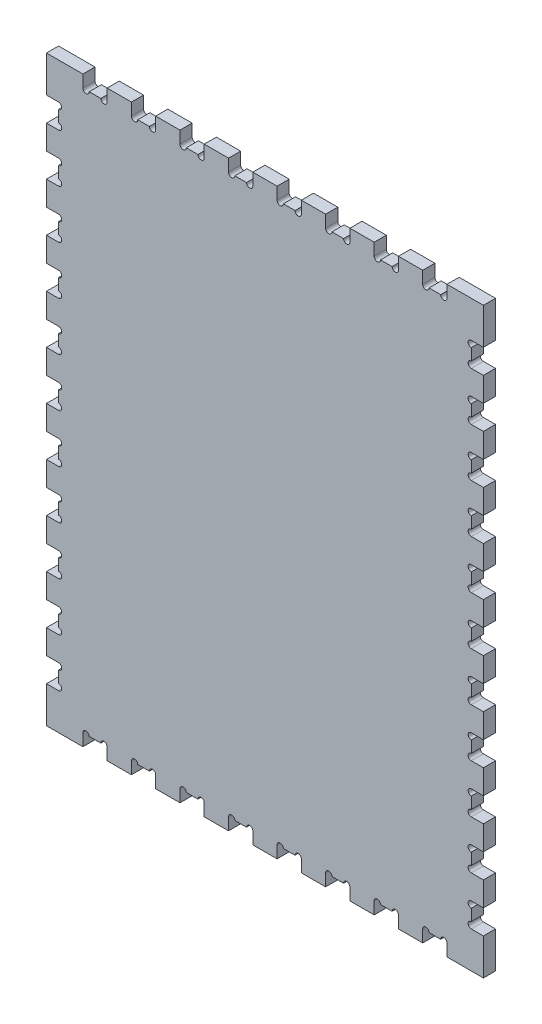
SolidWorks part; units mm, degrees
ref_plane "Front Plane" through (0, 0, 0) normal (0, 0, 1) x (1, 0, 0)
ref_plane "Top Plane" through (0, 0, 0) normal (0, 1, 0) x (1, 0, 0)
ref_plane "Right Plane" through (0, 0, 0) normal (1, 0, 0) x (0, 0, -1)
sketch "Sketch1" plane through (0, 0, 0) normal (0, 0, 1) x (1, 0, 0)
  line L1 (228.6, -304.8) -> (-228.6, -304.8)
  line L2 (228.6, -304.8) -> (228.6, 304.8)
  line L3 (228.6, 304.8) -> (-228.6, 304.8)
  line L4 (-228.6, -304.8) -> (-228.6, 304.8)
  line L5 (228.6, -304.8) -> (-228.6, 304.8) construction
  line L6 (228.6, 304.8) -> (-228.6, -304.8) construction
  line L9 (-203.2, 304.8) -> (-228.6, 304.8) construction
  point P0 (0, 0)
  point P7 (0, 0)
  dimension "D1" = 457.2
  dimension "D2" = 609.6
extrude "Boss-Extrude1" add sketch "Sketch1" along normal blind 12.7
sketch "Sketch2" plane through (0, 0, 12.7) normal (0, 0, 1) x (1, 0, 0)
  line L0 (228.6, 304.8) -> (-228.6, 304.8) construction
  line L1 (-190.5, 292.1) -> (-228.6, 292.1) construction
  line L2 (-190.5, 304.8) -> (-165.1, 304.8)
  line L3 (-190.5, 304.8) -> (-190.5, 292.1)
  line L4 (-190.5, 292.1) -> (-165.1, 292.1)
  line L5 (-165.1, 304.8) -> (-165.1, 292.1)
  line L6 (-228.6, 304.8) -> (-228.6, -304.8) construction
  circle A0 centre (-187.198, 292.1) radius 3.302
  circle A1 centre (-168.402, 292.1) radius 3.302
  point P13 (-200.025, 292.1)
  point P14 (-200.025, 292.1)
  line M10 (228.6, 304.8) -> (-228.6, 304.8)
  dimension "D4" = 6.604
  dimension "D5" = 6.604
  dimension "D1" = 25.4
  dimension "D2" = 12.7
  dimension "D3" = 38.1
extrude "Cut-Extrude1" cut sketch "Sketch2" against normal through all contours A1 L5 L3 A0 L4 M10 | L4 A0 | L4 A0 | L4 A1 | L4 A1
pattern_linear "LPattern1" count 8 spacing 50.8 along (1, 0, 0) of "Cut-Extrude1"
sketch "Sketch3" plane through (0, 0, 12.7) normal (0, 0, 1) x (1, 0, 0)
  line L0 (-228.6, 304.8) -> (-228.6, -304.8) construction
  line L1 (-228.6, 266.7) -> (-215.9, 266.7)
  line L2 (-228.6, 266.7) -> (-228.6, 241.3)
  line L3 (-228.6, 241.3) -> (-215.9, 241.3)
  line L4 (-215.9, 266.7) -> (-215.9, 241.3)
  line L5 (-215.9, 266.7) -> (-215.9, 304.8) construction
  line L7 (-190.5, 304.8) -> (-228.6, 304.8) construction
  circle A0 centre (-215.9, 263.398) radius 3.302
  circle A1 centre (-215.9, 244.602) radius 3.302
  dimension "D3" = 6.604
  dimension "D4" = 6.604
  dimension "D1" = 25.4
  dimension "D2" = 12.7
  dimension "D5" = 38.1
extrude "Cut-Extrude2" cut sketch "Sketch3" against normal through all contours A1 L4 A0 L1 L2 L3 | L4 A0 | L4 A1 | L4 A1 | L4 A0
pattern_linear "LPattern2" count 11 spacing 50.8 along (0, -1, 0) of "Cut-Extrude2"
ref_plane "Plane1" through (0, 0, 0) normal (1, 0, 0) x (0, 0, -1)
ref_plane "Plane2" through (0, 0, 0) normal (0, 1, 0) x (1, 0, 0)
mirror "Mirror1" about plane through (0, 0, 0) normal (1, 0, 0) of "LPattern2", "Cut-Extrude2"
mirror "Mirror2" about plane through (0, 0, 0) normal (0, 1, 0) of "LPattern1", "Cut-Extrude1"
